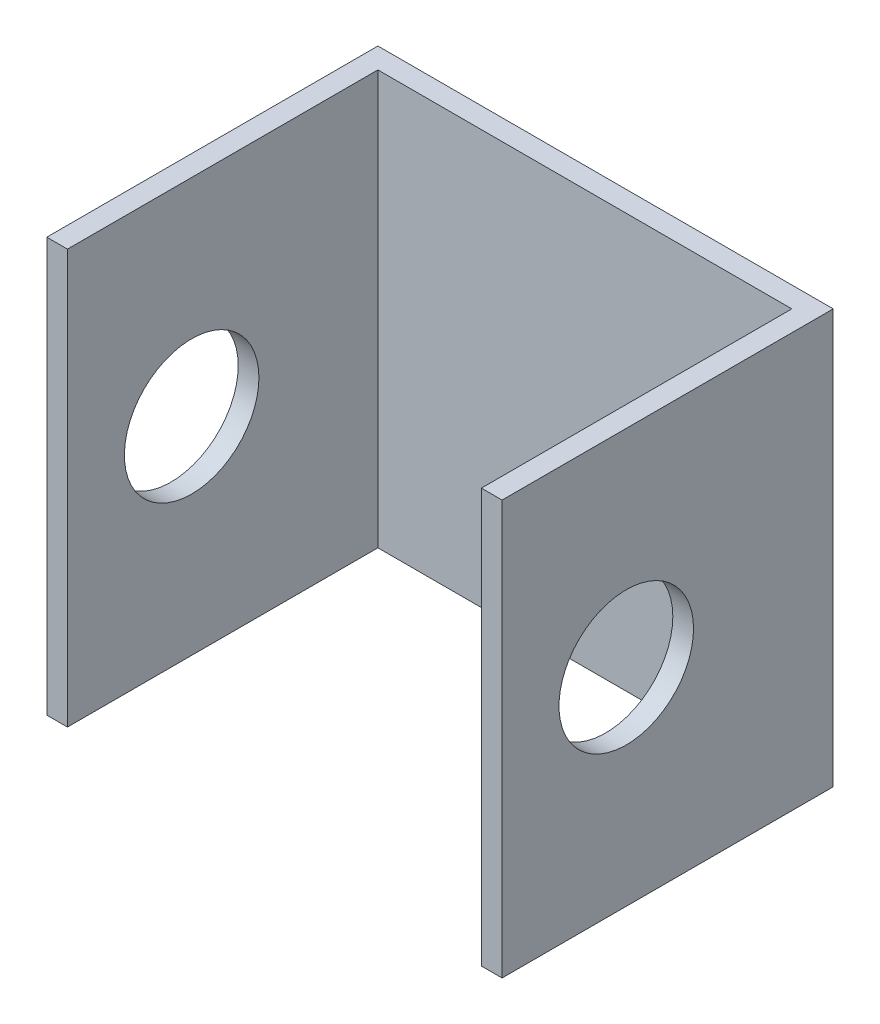
SolidWorks part; units mm, degrees
ref_plane "Front Plane" through (0, 0, 0) normal (0, 0, 1) x (1, 0, 0)
ref_plane "Top Plane" through (0, 0, 0) normal (0, 1, 0) x (1, 0, 0)
ref_plane "Right Plane" through (0, 0, 0) normal (1, 0, 0) x (0, 0, -1)
sketch "Sketch1" plane through (0, 0, 0) normal (0, 0, 1) x (1, 0, 0)
  line L1 (-11, -10) -> (11, -10)
  line L2 (-11, -10) -> (-11, 10)
  line L3 (-11, 10) -> (11, 10)
  line L4 (11, -10) -> (11, 10)
  line L5 (-11, -10) -> (11, 10) construction
  line L6 (-11, 10) -> (11, -10) construction
  point P0 (0, 0)
  dimension "D1" = 22
  dimension "D2" = 20
extrude "Boss-Extrude1" add sketch "Sketch1" along normal blind 1
sketch "Sketch2" plane through (0, 0, 1) normal (0, 0, 1) x (1, 0, 0)
  line L0 (-11, 10) -> (-11, -10)
  line L1 (-11, 10) -> (-10, 10)
  line L2 (-11, -10) -> (-10, -10)
  line L3 (-10, 10) -> (-10, -10)
  line L4 (11, 10) -> (11, -10)
  line L5 (11, 10) -> (10, 10)
  line L6 (11, -10) -> (10, -10)
  line L7 (10, 10) -> (10, -10)
  dimension "D1" = 1
  dimension "D2" = 1
extrude "Boss-Extrude2" add sketch "Sketch2" along normal blind 15
sketch "Sketch3" plane through (11, 0, 0) normal (1, 0, 0) x (0, 0, -1)
  line L0 (0, -10) -> (0, 10) construction
  circle A0 centre (-10, 0) radius 3.25
  dimension "D2" = 6.5
  dimension "D1" = 10
extrude "Cut-Extrude1" cut sketch "Sketch3" against normal through all
